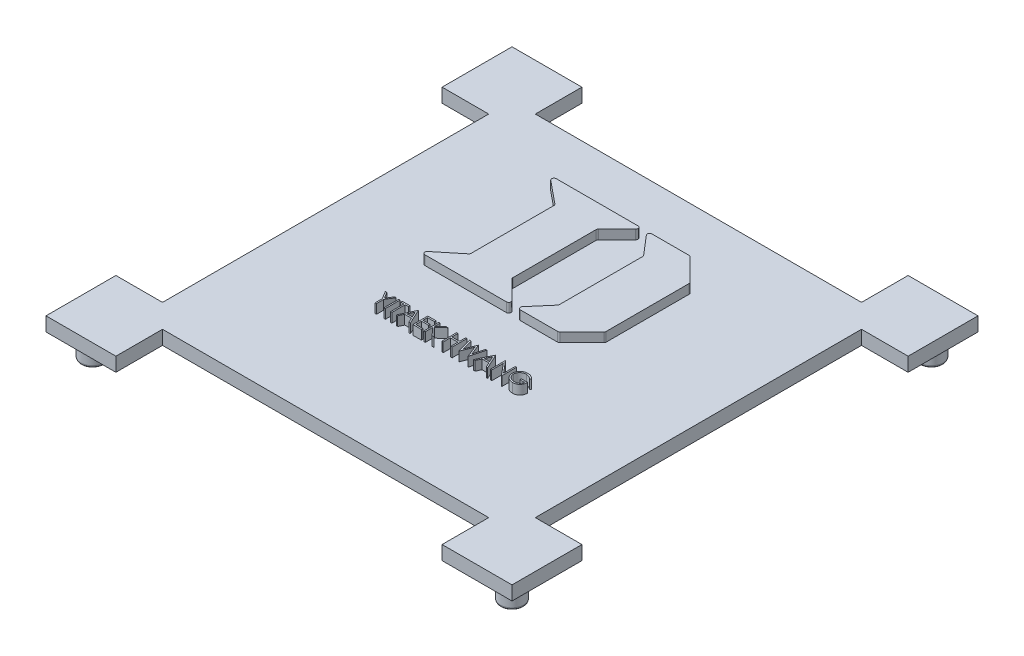
SolidWorks part; units mm, degrees
ref_plane "Front Plane" through (0, 0, 0) normal (0, 0, 1) x (1, 0, 0)
ref_plane "Top Plane" through (0, 0, 0) normal (0, 1, 0) x (1, 0, 0)
ref_plane "Right Plane" through (0, 0, 0) normal (1, 0, 0) x (0, 0, -1)
sketch "Sketch1" plane through (0, 0, 0) normal (0, 1, 0) x (1, 0, 0)
  line L0 (15, 10) -> (85, 10)
  line L1 (0, 0) -> (15, 0)
  line L2 (0, 0) -> (0, 15)
  line L3 (0, 100) -> (15, 100)
  line L4 (100, 0) -> (100, 15)
  line L7 (0, 15) -> (10, 15)
  line L8 (15, 0) -> (15, 10)
  line L9 (100, 0) -> (85, 0)
  line L11 (100, 15) -> (90, 15)
  line L12 (85, 0) -> (85, 10)
  line L13 (100, 100) -> (85, 100)
  line L14 (100, 100) -> (100, 85)
  line L15 (100, 85) -> (90, 85)
  line L16 (85, 100) -> (85, 90)
  line L18 (0, 100) -> (0, 85)
  line L19 (0, 85) -> (10, 85)
  line L20 (15, 100) -> (15, 90)
  line L21 (90, 15) -> (90, 85)
  line L22 (15, 90) -> (85, 90)
  line L23 (10, 85) -> (10, 15)
  dimension "D1" = 100
  dimension "D2" = 100
  dimension "D5" = 10
  dimension "D6" = 10
  dimension "D7" = 10
  dimension "D8" = 10
extrude "Boss-Extrude1" add sketch "Sketch1" along normal blind 3
sketch "Sketch2" plane through (0, 3, 0) normal (0, 1, 0) x (1, 0, 0)
  line L0 (10, 35.753) -> (90, 35.753) construction
  line L1 (10, 85) -> (10, 15) construction
  line L2 (90, 15) -> (90, 85) construction
  text T0 "YITAEK HWANG"
extrude "Boss-Extrude2" add sketch "Sketch2" along normal blind 2
sketch "Sketch4" plane through (0, 3, 0) normal (0, 1, 0) x (1, 0, 0)
  line L0 (50, 90) -> (50, 10) construction
  line L1 (85, 90) -> (15, 90) construction
  line L2 (15, 10) -> (85, 10) construction
  line L3 (50, 78.2365) -> (45, 73.2365)
  line L4 (45, 73.2365) -> (45, 55)
  line L5 (45, 55) -> (50, 50)
  line L6 (55, 73.2365) -> (50.7153, 78.2365)
  line L7 (55, 73.2365) -> (55, 55)
  line L8 (50.7153, 78.2365) -> (60, 78.2365)
  line L9 (36, 73.2365) -> (36, 55)
  line L10 (36, 73.2365) -> (29.8747, 78.2365)
  line L11 (29.8747, 78.2365) -> (50, 78.2365)
  line L12 (36, 55) -> (29.8747, 50)
  line L13 (29.8747, 50) -> (50, 50)
  line L14 (65, 55) -> (60, 50)
  line L15 (55, 55) -> (50.7153, 50)
  line L16 (65, 73.2365) -> (65, 55)
  line L17 (65, 73.2365) -> (60, 78.2365)
  line L18 (50.7153, 50) -> (60, 50)
  dimension "D1" = 5
  dimension "D2" = 5
  dimension "D3" = 5
  dimension "D4" = 9
  dimension "D5" = 10
extrude "Boss-Extrude6" add sketch "Sketch4" along normal blind 2 contours L12 L13 L5 L4 L3 L11 L10 L9 | L15 L18 L14 L16 L17 L8 L6 L7
fillet "Fillet1" radius 0.5 8 edges at (50, 4, -50) (45, 4, -55) (45, 4, -73.2365) (50, 4, -78.2365) (29.8747, 4, -50) (36, 4, -55) (36, 4, -73.2365) (29.8747, 4, -78.2365)
fillet "Fillet2" radius 0.5 8 edges at (60, 4, -78.2365) (65, 4, -73.2365) (65, 4, -55) (60, 4, -50) (50.7153, 4, -50) (55, 4, -55) (50.7153, 4, -78.2365) (55, 4, -73.2365)
sketch "Sketch5" plane through (0, 0, 0) normal (0, -1, 0) x (-1, 0, 0)
  line L0 (0, 15) -> (0, 0) construction
  line L1 (0, 0) -> (-15, 0) construction
  line L2 (-100, 0) -> (-100, 15) construction
  line L4 (-85, 0) -> (-100, 0) construction
  line L5 (-100, 85) -> (-100, 100) construction
  line L6 (-100, 100) -> (-85, 100) construction
  line L7 (-15, 100) -> (0, 100) construction
  line L8 (0, 100) -> (0, 85) construction
  circle A0 centre (-5, 5) radius 2.5
  circle A1 centre (-95, 5) radius 2.5
  circle A2 centre (-5, 95) radius 2.5
  circle A3 centre (-95, 95) radius 2.5
  dimension "D1" = 5
  dimension "D5" = 5
  dimension "D9" = 5
  dimension "D10" = 5
  dimension "D2" = 5
  dimension "D3" = 5
  dimension "D4" = 5
  dimension "D6" = 5
  dimension "D7" = 5
  dimension "D8" = 5
  dimension "D11" = 5
  dimension "D12" = 5
extrude "Boss-Extrude7" add sketch "Sketch5" along normal blind 5 contours A2 | A3 | A0 | A1
fillet "Fillet3" radius 0.5 4 edges at (5, -5, -97.5) (5, -5, -7.5) (95, -5, -97.5) (95, -5, -7.5)
